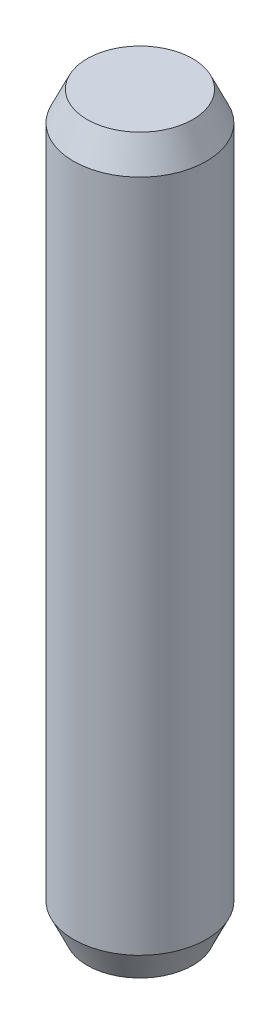
SolidWorks part; units mm, degrees
material "AISI Type 316L stainless steel"
ref_plane "Front Plane" through (0, 0, 0) normal (0, 0, 1) x (1, 0, 0)
ref_plane "Top Plane" through (0, 0, 0) normal (0, 1, 0) x (1, 0, 0)
ref_plane "Right Plane" through (0, 0, 0) normal (1, 0, 0) x (0, 0, -1)
sketch "Sketch1" plane through (0, 0, 0) normal (0, 1, 0) x (1, 0, 0)
  circle A0 centre (0, 0) radius 3.175
  dimension "D1" = 6.35
extrude "Boss-Extrude1" add sketch "Sketch1" along normal blind 35
chamfer "Chamfer1" distance 1.4 angle 25 2 edges at (0, 35, 3.175) (0, 0, 3.175)
